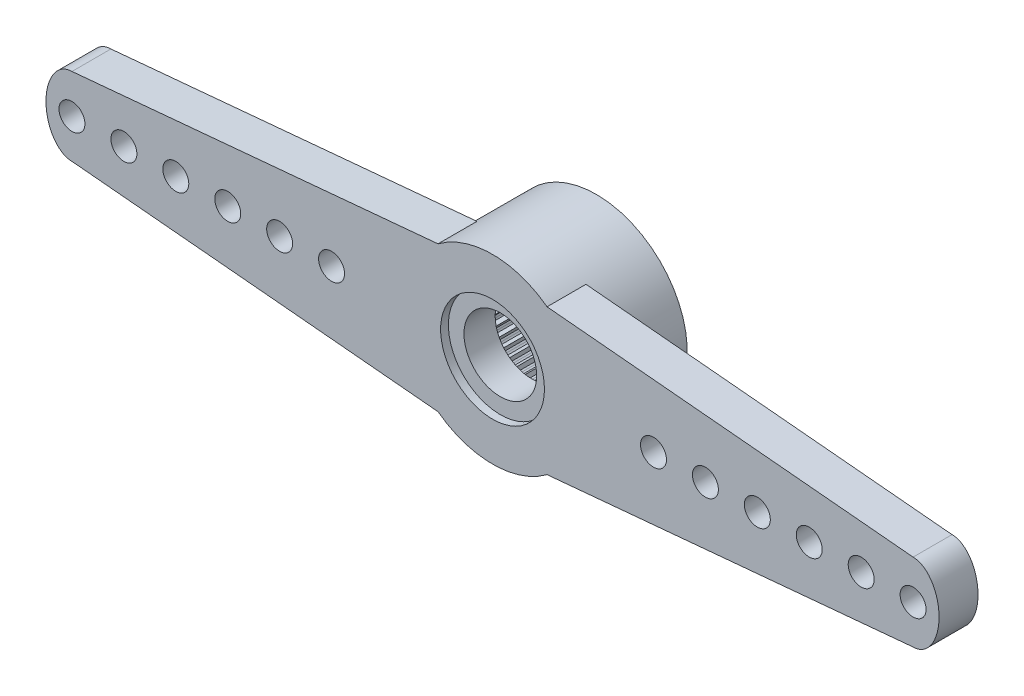
SolidWorks part; units mm, degrees
ref_plane "Alzado" through (0, 0, 0) normal (0, 0, 1) x (1, 0, 0)
ref_plane "Planta" through (0, 0, 0) normal (0, 1, 0) x (1, 0, 0)
ref_plane "Vista lateral" through (0, 0, 0) normal (1, 0, 0) x (0, 0, -1)
sketch "Croquis1" plane through (0, 0, 0) normal (0, 0, 1) x (1, 0, 0)
  line L0 (-17.2, 0) -> (17.2, 0) construction
  line L1 (0, -3.5) -> (0, 3.5) construction
  line L2 (-2.1, 2.8) -> (-2.1, -2.8) construction
  line L3 (2.1, 2.8) -> (2.1, -2.8) construction
  line L4 (-15.2, 0) -> (19.2, 0) construction
  line L5 (-13.2, 0) -> (21.2, 0) construction
  line L6 (-11.2, 0) -> (23.2, 0) construction
  line L7 (-9.2, 0) -> (25.2, 0) construction
  line L8 (-7.2, 0) -> (27.2, 0) construction
  line L9 (-16.2, -1.5) -> (-16.2, 1.5) construction
  line L10 (-2.1, 2.8) -> (-16.2, 1.5)
  line L11 (-2.1, -2.8) -> (-16.2, -1.5)
  line L12 (2.1, -2.8) -> (16.2, -1.5)
  line L13 (2.1, 2.8) -> (16.2, 1.5)
  arc A0 (-2.1, -2.8) -> (2.1, -2.8) centre (0, 0) ccw
  circle A1 centre (-16.2, 0) radius 0.5
  circle A2 centre (-14.2, 0) radius 0.5
  circle A3 centre (-12.2, 0) radius 0.5
  circle A4 centre (-10.2, 0) radius 0.5
  circle A5 centre (-8.2, 0) radius 0.5
  circle A6 centre (-6.2, 0) radius 0.5
  circle A7 centre (6.2, 0) radius 0.5
  circle A8 centre (8.2, 0) radius 0.5
  circle A9 centre (10.2, 0) radius 0.5
  circle A10 centre (12.2, 0) radius 0.5
  circle A11 centre (14.2, 0) radius 0.5
  circle A12 centre (16.2, 0) radius 0.5
  arc A13 (2.1, 2.8) -> (-2.1, 2.8) centre (0, 0) ccw
  ellipse E0 centre (-16.2, 0) end of major axis (-16.2, -1.5) minor radius 1 (-16.2, 1.5) -> (-16.2, -1.5) ccw
  ellipse E1 centre (16.2, 0) end of major axis (16.2, -1.5) minor radius 1 (16.2, 1.5) -> (16.2, -1.5) cw
  point P7 (0, 0)
  point P8 (0, 0)
  point P50 (-16.2, 0)
  dimension "D4" = 1
  dimension "D5" = 1
  dimension "D1" = 34.4
  dimension "D2" = 7
  dimension "D3" = 5.6
  dimension "D7" = 3
  dimension "D6" = 6
extrude "Saliente-Extruir1" add sketch "Croquis1" along normal blind 1.5
sketch "Croquis3" plane through (0, 0, 0) normal (0, 0, -1) x (-1, 0, 0)
  circle A0 centre (0, 0) radius 3.5
  circle A1 centre (0, 0) radius 2.25
  dimension "D1" = 7
  dimension "D2" = 4.5
extrude "Saliente-Extruir2" add sketch "Croquis3" along normal blind 2.5
sketch "Croquis4" plane through (0, 0, 0) normal (0, 0, -1) x (-1, 0, 0)
  circle A0 centre (0, 0) radius 1.4
  dimension "D1" = 2.8
extrude "Cortar-Extruir1" cut sketch "Croquis4" against normal through all contours A0
sketch "Croquis5" plane through (0, 0, 1.5) normal (0, 0, 1) x (1, 0, 0)
  circle A0 centre (0, 0) radius 2
  dimension "D1" = 4
extrude "Cortar-Extruir2" cut sketch "Croquis5" against normal blind 0.3
sketch "Croquis6" plane through (0, 0, -2.5) normal (0, 0, -1) x (-1, 0, 0)
  line L0 (0, 0) -> (0, -2.4) construction
  line L1 (0, -2.25) -> (0.1004, -2.3979)
  line L2 (0, -2.25) -> (-0.1004, -2.3979)
  line L3 (0.1004, -2.3979) -> (0.1674, -2.3942)
  line L4 (-0.1004, -2.3979) -> (-0.1674, -2.3942)
  line L5 (-0.4331, -2.3606) -> (-0.4988, -2.3476)
  line L6 (-0.313, -2.2281) -> (-0.4331, -2.3606)
  line L7 (-0.313, -2.2281) -> (-0.2342, -2.3885)
  line L8 (-0.2342, -2.3885) -> (-0.1674, -2.3942)
  line L9 (-0.7573, -2.2773) -> (-0.8206, -2.2553)
  line L10 (-0.62, -2.1629) -> (-0.7573, -2.2773)
  line L11 (-0.62, -2.1629) -> (-0.5642, -2.3327)
  line L12 (-0.5642, -2.3327) -> (-0.4988, -2.3476)
  line L13 (-1.0668, -2.1498) -> (-1.1264, -2.1192)
  line L14 (-0.9149, -2.0555) -> (-1.0668, -2.1498)
  line L15 (-0.9149, -2.0555) -> (-0.8833, -2.2315)
  line L16 (-0.8833, -2.2315) -> (-0.8206, -2.2553)
  line L17 (-1.3555, -1.9804) -> (-1.4103, -1.9418)
  line L18 (-1.192, -1.9082) -> (-1.3555, -1.9804)
  line L19 (-1.192, -1.9082) -> (-1.1852, -2.0869)
  line L20 (-1.1852, -2.0869) -> (-1.1264, -2.1192)
  line L21 (-1.6178, -1.7725) -> (-1.6667, -1.7266)
  line L22 (-1.4458, -1.7238) -> (-1.6178, -1.7725)
  line L23 (-1.4458, -1.7238) -> (-1.464, -1.9016)
  line L24 (-1.464, -1.9016) -> (-1.4103, -1.9418)
  line L25 (-1.8487, -1.5301) -> (-1.8907, -1.4778)
  line L26 (-1.6716, -1.5058) -> (-1.8487, -1.5301)
  line L27 (-1.6716, -1.5058) -> (-1.7143, -1.6794)
  line L28 (-1.7143, -1.6794) -> (-1.6667, -1.7266)
  line L29 (-2.0435, -1.2579) -> (-2.0779, -1.2003)
  line L30 (-1.8648, -1.2585) -> (-2.0435, -1.2579)
  line L31 (-1.8648, -1.2585) -> (-1.9312, -1.4245)
  line L32 (-1.9312, -1.4245) -> (-1.8907, -1.4778)
  line L33 (-2.1986, -0.9613) -> (-2.2246, -0.8995)
  line L34 (-2.0217, -0.9867) -> (-2.1986, -0.9613)
  line L35 (-2.0217, -0.9867) -> (-2.1106, -1.1418)
  line L36 (-2.1106, -1.1418) -> (-2.0779, -1.2003)
  line L37 (-2.3109, -0.6459) -> (-2.3281, -0.5811)
  line L38 (-2.1392, -0.6958) -> (-2.3109, -0.6459)
  line L39 (-2.1392, -0.6958) -> (-2.2489, -0.837)
  line L40 (-2.2489, -0.837) -> (-2.2246, -0.8995)
  line L41 (-2.3782, -0.318) -> (-2.3862, -0.2515)
  line L42 (-2.2152, -0.3913) -> (-2.3782, -0.318)
  line L43 (-2.2152, -0.3913) -> (-2.3434, -0.5159)
  line L44 (-2.3434, -0.5159) -> (-2.3281, -0.5811)
  line L45 (-2.3993, 0.016) -> (-2.3979, 0.0831)
  line L46 (-2.248, -0.0792) -> (-2.3993, 0.016)
  line L47 (-2.248, -0.0792) -> (-2.3923, -0.1847)
  line L48 (-2.3923, -0.1847) -> (-2.3862, -0.2515)
  line L49 (-2.3736, 0.3498) -> (-2.3629, 0.416)
  line L50 (-2.237, 0.2344) -> (-2.3736, 0.3498)
  line L51 (-2.237, 0.2344) -> (-2.3946, 0.15)
  line L52 (-2.3946, 0.15) -> (-2.3979, 0.0831)
  line L53 (-2.3017, 0.6767) -> (-2.2819, 0.7408)
  line L54 (-2.1825, 0.5435) -> (-2.3017, 0.6767)
  line L55 (-2.1825, 0.5435) -> (-2.3503, 0.4818)
  line L56 (-2.3503, 0.4818) -> (-2.3629, 0.416)
  line L57 (-2.185, 0.9905) -> (-2.1565, 1.0511)
  line L58 (-2.0855, 0.8419) -> (-2.185, 0.9905)
  line L59 (-2.0855, 0.8419) -> (-2.2603, 0.8042)
  line L60 (-2.2603, 0.8042) -> (-2.2819, 0.7408)
  line L61 (-2.0258, 1.2849) -> (-1.9891, 1.341)
  line L62 (-1.948, 1.124) -> (-2.0258, 1.2849)
  line L63 (-1.948, 1.124) -> (-2.1263, 1.111)
  line L64 (-2.1263, 1.111) -> (-2.1565, 1.0511)
  line L65 (-1.8272, 1.5543) -> (-1.783, 1.6048)
  line L66 (-1.7725, 1.3841) -> (-1.8272, 1.5543)
  line L67 (-1.7725, 1.3841) -> (-1.9509, 1.3961)
  line L68 (-1.9509, 1.3961) -> (-1.9891, 1.341)
  line L69 (-1.593, 1.7935) -> (-1.5423, 1.8373)
  line L70 (-1.5625, 1.6173) -> (-1.593, 1.7935)
  line L71 (-1.5625, 1.6173) -> (-1.7375, 1.654)
  line L72 (-1.7375, 1.654) -> (-1.783, 1.6048)
  line L73 (-1.3278, 1.9978) -> (-1.2714, 2.0341)
  line L74 (-1.3221, 1.8191) -> (-1.3278, 1.9978)
  line L75 (-1.3221, 1.8191) -> (-1.4903, 1.8797)
  line L76 (-1.4903, 1.8797) -> (-1.5423, 1.8373)
  line L77 (-1.0367, 2.1631) -> (-0.9759, 2.1912)
  line L78 (-1.056, 1.9854) -> (-1.0367, 2.1631)
  line L79 (-1.056, 1.9854) -> (-1.2141, 2.0688)
  line L80 (-1.2141, 2.0688) -> (-1.2714, 2.0341)
  line L81 (-0.7255, 2.2863) -> (-0.6613, 2.3057)
  line L82 (-0.7693, 2.113) -> (-0.7255, 2.2863)
  line L83 (-0.7693, 2.113) -> (-0.9143, 2.2176)
  line L84 (-0.9143, 2.2176) -> (-0.9759, 2.1912)
  line L85 (-0.4002, 2.365) -> (-0.3339, 2.3753)
  line L86 (-0.4677, 2.1995) -> (-0.4002, 2.365)
  line L87 (-0.4677, 2.1995) -> (-0.5967, 2.3233)
  line L88 (-0.5967, 2.3233) -> (-0.6613, 2.3057)
  line L89 (-0.067, 2.3977) -> (0, 2.3986)
  line L90 (-0.1569, 2.2432) -> (-0.067, 2.3977)
  line L91 (-0.1569, 2.2432) -> (-0.2674, 2.3837)
  line L92 (-0.2674, 2.3837) -> (-0.3339, 2.3753)
  line L93 (0.2674, 2.3837) -> (0.3339, 2.3753)
  line L94 (0.1569, 2.2432) -> (0.2674, 2.3837)
  line L95 (0.1569, 2.2432) -> (0.067, 2.3977)
  line L96 (0.067, 2.3977) -> (0, 2.3986)
  line L97 (0.5967, 2.3233) -> (0.6613, 2.3057)
  line L98 (0.4677, 2.1995) -> (0.5967, 2.3233)
  line L99 (0.4677, 2.1995) -> (0.4002, 2.365)
  line L100 (0.4002, 2.365) -> (0.3339, 2.3753)
  line L101 (0.9143, 2.2176) -> (0.9759, 2.1912)
  line L102 (0.7693, 2.113) -> (0.9143, 2.2176)
  line L103 (0.7693, 2.113) -> (0.7255, 2.2863)
  line L104 (0.7255, 2.2863) -> (0.6613, 2.3057)
  line L105 (1.2141, 2.0688) -> (1.2714, 2.0341)
  line L106 (1.056, 1.9854) -> (1.2141, 2.0688)
  line L107 (1.056, 1.9854) -> (1.0367, 2.1631)
  line L108 (1.0367, 2.1631) -> (0.9759, 2.1912)
  line L109 (1.4903, 1.8797) -> (1.5423, 1.8373)
  line L110 (1.3221, 1.8191) -> (1.4903, 1.8797)
  line L111 (1.3221, 1.8191) -> (1.3278, 1.9978)
  line L112 (1.3278, 1.9978) -> (1.2714, 2.0341)
  line L113 (1.7375, 1.654) -> (1.783, 1.6048)
  line L114 (1.5625, 1.6173) -> (1.7375, 1.654)
  line L115 (1.5625, 1.6173) -> (1.593, 1.7935)
  line L116 (1.593, 1.7935) -> (1.5423, 1.8373)
  line L117 (1.9509, 1.3961) -> (1.9891, 1.341)
  line L118 (1.7725, 1.3841) -> (1.9509, 1.3961)
  line L119 (1.7725, 1.3841) -> (1.8272, 1.5543)
  line L120 (1.8272, 1.5543) -> (1.783, 1.6048)
  line L121 (2.1263, 1.111) -> (2.1565, 1.0511)
  line L122 (1.948, 1.124) -> (2.1263, 1.111)
  line L123 (1.948, 1.124) -> (2.0258, 1.2849)
  line L124 (2.0258, 1.2849) -> (1.9891, 1.341)
  line L125 (2.2603, 0.8042) -> (2.2819, 0.7408)
  line L126 (2.0855, 0.8419) -> (2.2603, 0.8042)
  line L127 (2.0855, 0.8419) -> (2.185, 0.9905)
  line L128 (2.185, 0.9905) -> (2.1565, 1.0511)
  line L129 (2.3503, 0.4818) -> (2.3629, 0.416)
  line L130 (2.1825, 0.5435) -> (2.3503, 0.4818)
  line L131 (2.1825, 0.5435) -> (2.3017, 0.6767)
  line L132 (2.3017, 0.6767) -> (2.2819, 0.7408)
  line L133 (2.3946, 0.15) -> (2.3979, 0.0831)
  line L134 (2.237, 0.2344) -> (2.3946, 0.15)
  line L135 (2.237, 0.2344) -> (2.3736, 0.3498)
  line L136 (2.3736, 0.3498) -> (2.3629, 0.416)
  line L137 (2.3923, -0.1847) -> (2.3862, -0.2515)
  line L138 (2.248, -0.0792) -> (2.3923, -0.1847)
  line L139 (2.248, -0.0792) -> (2.3993, 0.016)
  line L140 (2.3993, 0.016) -> (2.3979, 0.0831)
  line L141 (2.3434, -0.5159) -> (2.3281, -0.5811)
  line L142 (2.2152, -0.3913) -> (2.3434, -0.5159)
  line L143 (2.2152, -0.3913) -> (2.3782, -0.318)
  line L144 (2.3782, -0.318) -> (2.3862, -0.2515)
  line L145 (2.2489, -0.837) -> (2.2246, -0.8995)
  line L146 (2.1392, -0.6958) -> (2.2489, -0.837)
  line L147 (2.1392, -0.6958) -> (2.3109, -0.6459)
  line L148 (2.3109, -0.6459) -> (2.3281, -0.5811)
  line L149 (2.1106, -1.1418) -> (2.0779, -1.2003)
  line L150 (2.0217, -0.9867) -> (2.1106, -1.1418)
  line L151 (2.0217, -0.9867) -> (2.1986, -0.9613)
  line L152 (2.1986, -0.9613) -> (2.2246, -0.8995)
  line L153 (1.9312, -1.4245) -> (1.8907, -1.4778)
  line L154 (1.8648, -1.2585) -> (1.9312, -1.4245)
  line L155 (1.8648, -1.2585) -> (2.0435, -1.2579)
  line L156 (2.0435, -1.2579) -> (2.0779, -1.2003)
  line L157 (1.7143, -1.6794) -> (1.6667, -1.7266)
  line L158 (1.6716, -1.5058) -> (1.7143, -1.6794)
  line L159 (1.6716, -1.5058) -> (1.8487, -1.5301)
  line L160 (1.8487, -1.5301) -> (1.8907, -1.4778)
  line L161 (1.464, -1.9016) -> (1.4103, -1.9418)
  line L162 (1.4458, -1.7238) -> (1.464, -1.9016)
  line L163 (1.4458, -1.7238) -> (1.6178, -1.7725)
  line L164 (1.6178, -1.7725) -> (1.6667, -1.7266)
  line L165 (1.1852, -2.0869) -> (1.1264, -2.1192)
  line L166 (1.192, -1.9082) -> (1.1852, -2.0869)
  line L167 (1.192, -1.9082) -> (1.3555, -1.9804)
  line L168 (1.3555, -1.9804) -> (1.4103, -1.9418)
  line L169 (0.8833, -2.2315) -> (0.8206, -2.2553)
  line L170 (0.9149, -2.0555) -> (0.8833, -2.2315)
  line L171 (0.9149, -2.0555) -> (1.0668, -2.1498)
  line L172 (1.0668, -2.1498) -> (1.1264, -2.1192)
  line L173 (0.5642, -2.3327) -> (0.4988, -2.3476)
  line L174 (0.62, -2.1629) -> (0.5642, -2.3327)
  line L175 (0.62, -2.1629) -> (0.7573, -2.2773)
  line L176 (0.7573, -2.2773) -> (0.8206, -2.2553)
  line L177 (0.2342, -2.3885) -> (0.1674, -2.3942)
  line L178 (0.313, -2.2281) -> (0.2342, -2.3885)
  line L179 (0.313, -2.2281) -> (0.4331, -2.3606)
  line L180 (0.4331, -2.3606) -> (0.4988, -2.3476)
  circle A0 centre (0, 0) radius 2.25 construction
  circle A1 centre (0, 0) radius 2.25 construction
  circle A2 centre (0, 0) radius 2.4 construction
  point P233 (0, -0.0007)
  dimension "D1" = 0.15
  dimension "D2" = 45
extrude "Cortar-Extruir4" cut sketch "Croquis6" against normal blind 2
